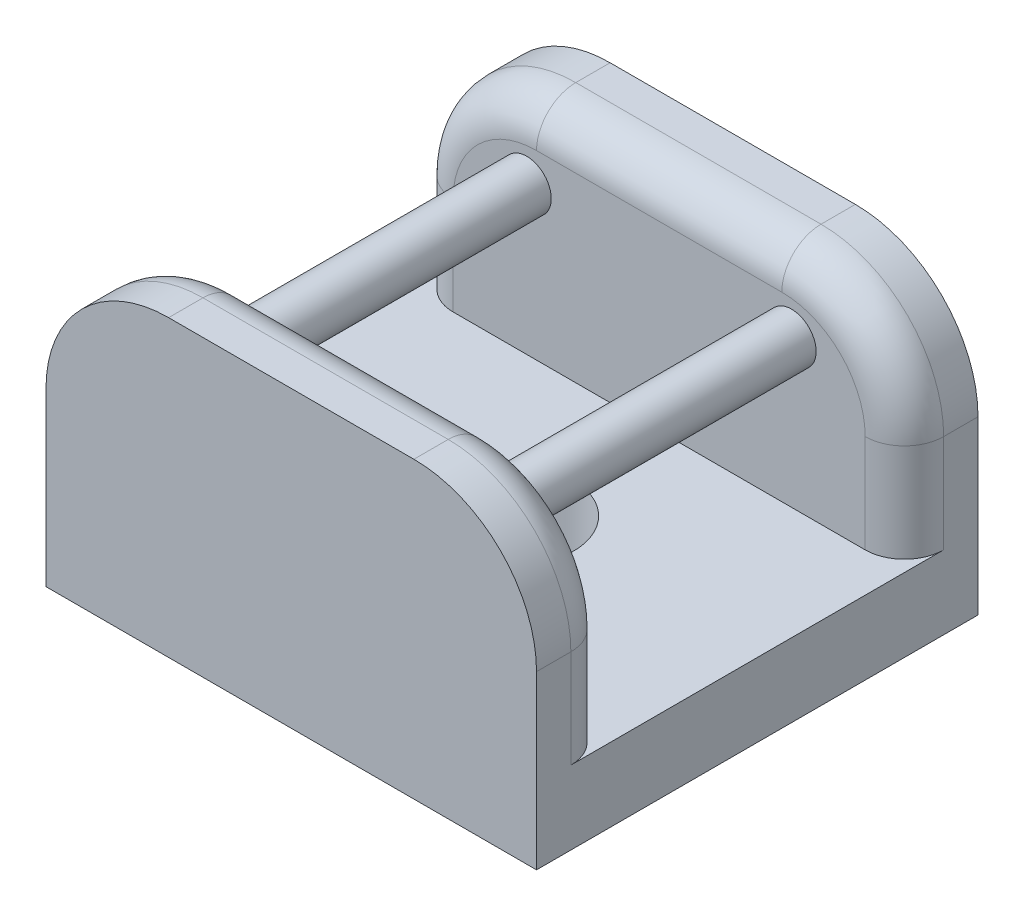
SolidWorks part; units mm, degrees
ref_plane "Front Plane" through (0, 0, 0) normal (0, 0, 1) x (1, 0, 0)
ref_plane "Top Plane" through (0, 0, 0) normal (0, 1, 0) x (1, 0, 0)
ref_plane "Right Plane" through (0, 0, 0) normal (1, 0, 0) x (0, 0, -1)
sketch "Sketch1" plane through (0, 0, 0) normal (1, 0, 0) x (0, 0, -1)
  line L0 (0, 0) -> (0, 60)
  line L1 (0, 60) -> (15, 60)
  line L2 (15, 60) -> (15, 15)
  line L3 (15, 15) -> (75, 15)
  line L4 (75, 15) -> (75, 60)
  line L5 (75, 60) -> (90, 60)
  line L6 (90, 60) -> (90, 0)
  line L7 (90, 0) -> (0, 0)
  line L8 (15, 15) -> (15, 0) construction
  dimension "D1" = 60
  dimension "D2" = 60
  dimension "D3" = 15
extrude "Boss-Extrude1" add sketch "Sketch1" along normal blind 100
sketch "Sketch2" plane through (0, 0, -15) normal (0, 0, -1) x (-1, 0, 0)
  line L0 (-100, 15) -> (0, 15) construction
  line L1 (-23, 45) -> (-77, 45) construction
  line L2 (-100, 60) -> (0, 60) construction
  line L3 (0, 60) -> (-100, 60) construction
  circle A0 centre (-77, 45) radius 5
  circle A1 centre (-23, 45) radius 5
  point P9 (-50, 60)
  point P13 (-50, 45)
  dimension "D2" = 10
  dimension "D1" = 30
  dimension "D3" = 54
extrude "Boss-Extrude2" add sketch "Sketch2" along normal up to surface (60 mm away) up to face at (50, 37.5, -75)
sketch "Sketch3" plane through (0, 0, 0) normal (0, -1, 0) x (1, 0, 0)
  line L0 (0, 0) -> (0, -90) construction
  line L1 (100, 0) -> (0, 0) construction
  circle A0 centre (50, -45) radius 12.5
  point P5 (0, -45)
  point P9 (50, 0)
  dimension "D1" = 25
extrude "Cut-Extrude1" cut sketch "Sketch3" against normal through all
sketch "Sketch4" plane through (0, 0, -90) normal (0, 0, -1) x (-1, 0, 0)
  line L0 (-100, 60) -> (0, 60) construction
  line L1 (-100, 0) -> (-100, 60) construction
  line L2 (-50, 0) -> (-50, 60) construction
  line L3 (-100, 0) -> (0, 0) construction
  circle A0 centre (-75, 35) radius 25
  circle A1 centre (-25, 35) radius 25
  line M3 (0, 0) -> (0, 60)
  line M4 (0, 60) -> (-100, 60)
  line M5 (-100, 60) -> (-100, 0)
  dimension "D1" = 50
extrude "Cut-Extrude2" cut sketch "Sketch4" against normal through all contours A0 M4 M5 | A1 M4 M3
fillet "Fillet1" radius 8 10 edges at (100, 25, -15) (0, 25, -15) (7.3223, 52.6777, -15) (50, 60, -15) (0, 25, -75) (7.3223, 52.6777, -75) (50, 60, -75) (100, 25, -75) (92.6777, 52.6777, -15) (92.6777, 52.6777, -75)
